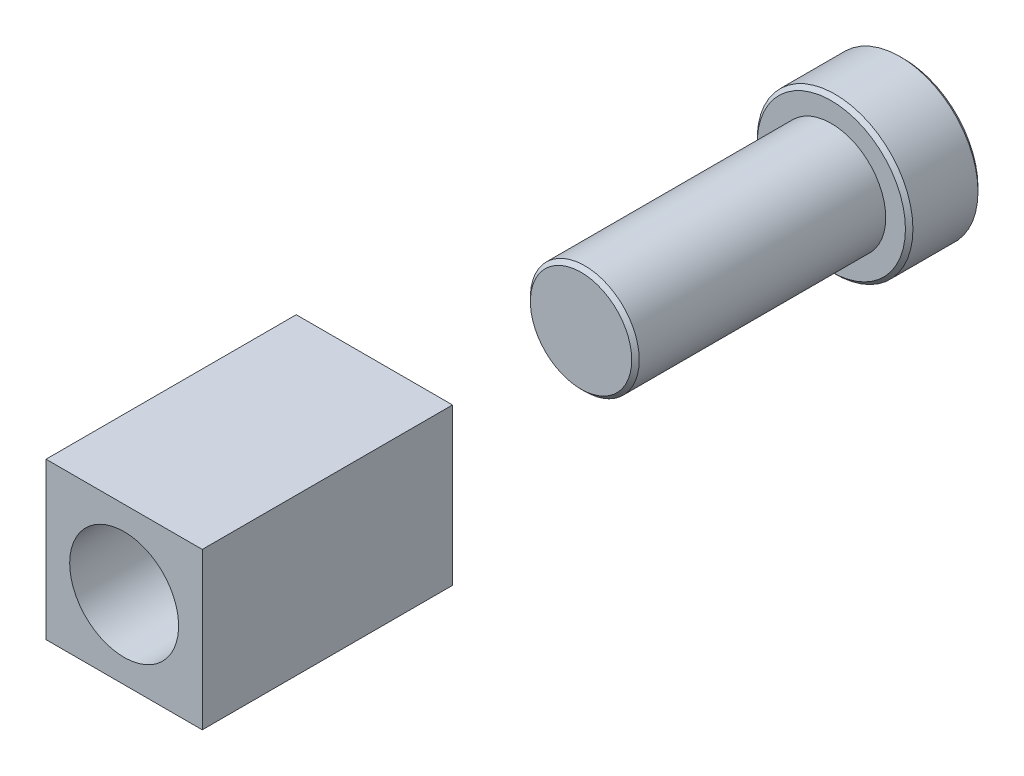
SolidWorks part; units mm, degrees
ref_plane "Front Plane" through (0, 0, 0) normal (0, 0, 1) x (1, 0, 0)
ref_plane "Top Plane" through (0, 0, 0) normal (0, 1, 0) x (1, 0, 0)
ref_plane "Right Plane" through (0, 0, 0) normal (1, 0, 0) x (0, 0, -1)
sketch "Sketch1" plane through (0, 0, 0) normal (0, 0, 1) x (1, 0, 0)
  circle A0 centre (0, 0) radius 15.8115
  dimension "D1" = 31.623
extrude "Boss-Extrude1" add sketch "Sketch1" along normal blind 14.732
sketch "Sketch2" plane through (0, 0, 14.732) normal (0, 0, 1) x (1, 0, 0)
  circle A0 centre (0, 0) radius 11.049
  dimension "D1" = 22.098
extrude "Boss-Extrude2" add sketch "Sketch2" along normal blind 50.8
ref_plane "Plane1" through (0, 0, 107.4833) normal (0, 0, 1) x (1, 0, 0)
sketch "Sketch3" plane through (0, 0, 107.4833) normal (0, 0, 1) x (1, 0, 0)
  line L0 (15.8613, -15.8613) -> (-15.8613, 15.8613) construction
  line L1 (-15.8613, 15.8613) -> (15.8613, 15.8613)
  line L2 (-15.8613, 15.8613) -> (-15.8613, -15.8613)
  line L3 (-15.8613, -15.8613) -> (15.8613, -15.8613)
  line L4 (15.8613, 15.8613) -> (15.8613, -15.8613)
extrude "Boss-Extrude3" add sketch "Sketch3" along normal blind 50.8 separate body
sketch "Sketch4" plane through (0, 0, 107.4833) normal (0, 0, -1) x (-1, 0, 0)
  circle A0 centre (0, 0) radius 11.0553
  dimension "D1" = 22.1107
extrude "Cut-Extrude1" cut sketch "Sketch4" against normal through all
chamfer "Chamfer1" distance 0.762 angle 45 3 edges at (15.8115, 0, 0) (15.8115, 0, 14.732) (11.049, 0, 65.532)
equation "\"Pin shaft diam\"= .87"
equation "\"Base length\"= \"D1@Boss-Extrude3\""
equation "\"D1@Sketch1\"= \"Pin shaft diam\" + .375"
equation "\"D1@Boss-Extrude1\"= \"Pin shaft diam\" / 1.5"
equation "\"D1@Boss-Extrude2\"= \"Base length\""
equation "\"D1@Sketch4\"= \"Pin shaft diam\" + .0005"
equation "\"D1@Sketch2\"= \"Pin shaft diam\""
equation "\"Chamfer1\"= IIF ( \"Pin shaft diam\" < 1mm , \"suppressed\" , \"unsuppressed\" )"
